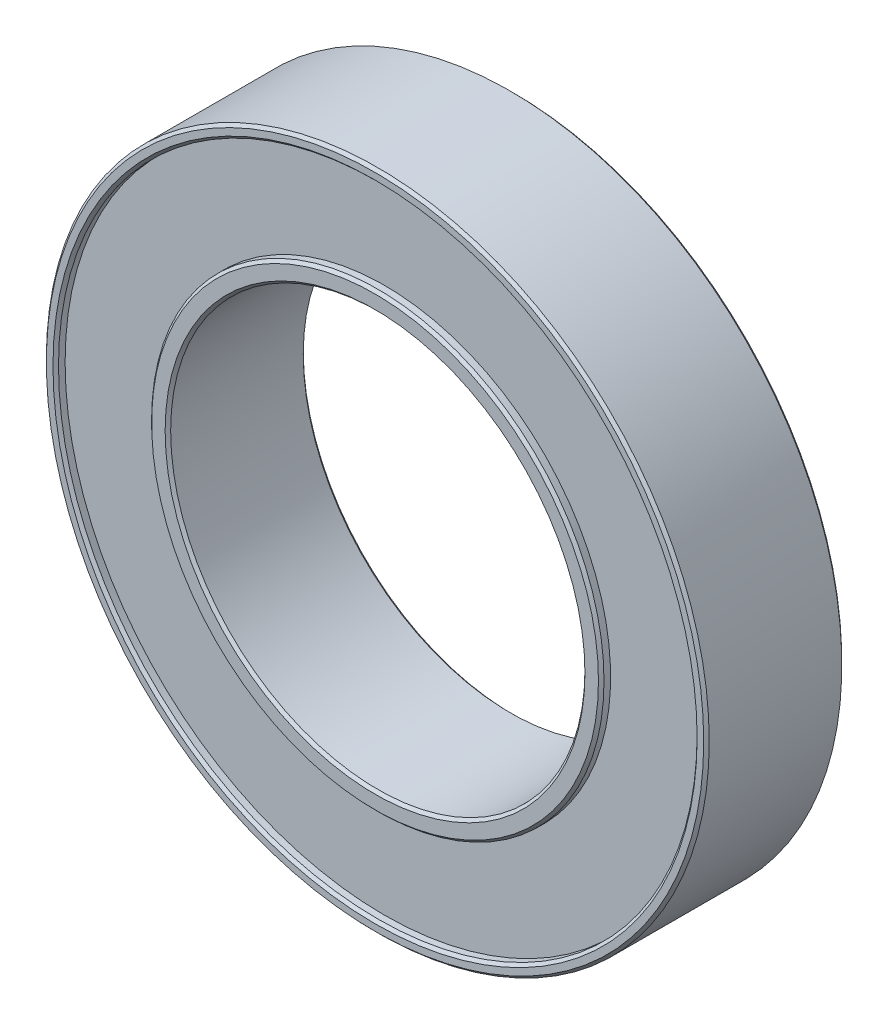
SolidWorks part; units mm, degrees
ref_plane "Front Plane" through (0, 0, 0) normal (0, 0, 1) x (1, 0, 0)
ref_plane "Top Plane" through (0, 0, 0) normal (0, 1, 0) x (1, 0, 0)
ref_plane "Right Plane" through (0, 0, 0) normal (1, 0, 0) x (0, 0, -1)
ref_axis "Axis1" through (0, 0, -19.0783) along (0, 0, 1)
sketch "Sketch1" plane through (0, 0, 0) normal (1, 0, 0) x (0, 0, -1)
  line L0 (19.0783, 0) -> (-24.5011, 0) construction
  line L1 (-2.5, 12) -> (2.5, 12)
  line L2 (-2.5, 12) -> (-2.5, 7.5) construction
  line L3 (-2.5, 7.5) -> (2.5, 7.5)
  line L4 (2.5, 12) -> (2.5, 11.5609)
  line L5 (-2.5, 12) -> (2.5, 7.5) construction
  line L6 (-2.5, 7.5) -> (2.5, 12) construction
  line L7 (0, 9.75) -> (0, 0) construction
  line L8 (2.5, 8.1894) -> (2.5, 7.5)
  line L9 (2.5, 11.5609) -> (2.1603, 11.5609)
  line L10 (-2.5, 8.1894) -> (-2.5, 7.5)
  line L11 (2.5, 8.1894) -> (2.1603, 8.1894)
  line L12 (2.1603, 11.5609) -> (2.1603, 8.1894)
  line L13 (-2.5, 8.1894) -> (-2.1603, 8.1894)
  line L14 (-2.1603, 11.5609) -> (-2.1603, 8.1894)
  line L15 (-2.5, 11.5609) -> (-2.1603, 11.5609)
  line L16 (-2.5, 12) -> (-2.5, 11.5609)
  point P0 (0, 9.75)
  dimension "D1" = 12
  dimension "D2" = 5
  dimension "D3" = 7.5
revolve "Revolve1" add sketch "Sketch1" angle 360 about axis through (0, 0, -19.0783) along (0, 0, 1)
chamfer "Chamfer1" distance 0.1 angle 45 8 edges at (-7.5, 0, -2.5) (-7.5, 0, 2.5) (-12, 0, 2.5) (-12, 0, -2.5) (-11.5609, 0, -2.5) (-8.1894, 0, -2.5) (-11.5609, 0, 2.5) (-8.1894, 0, 2.5)
